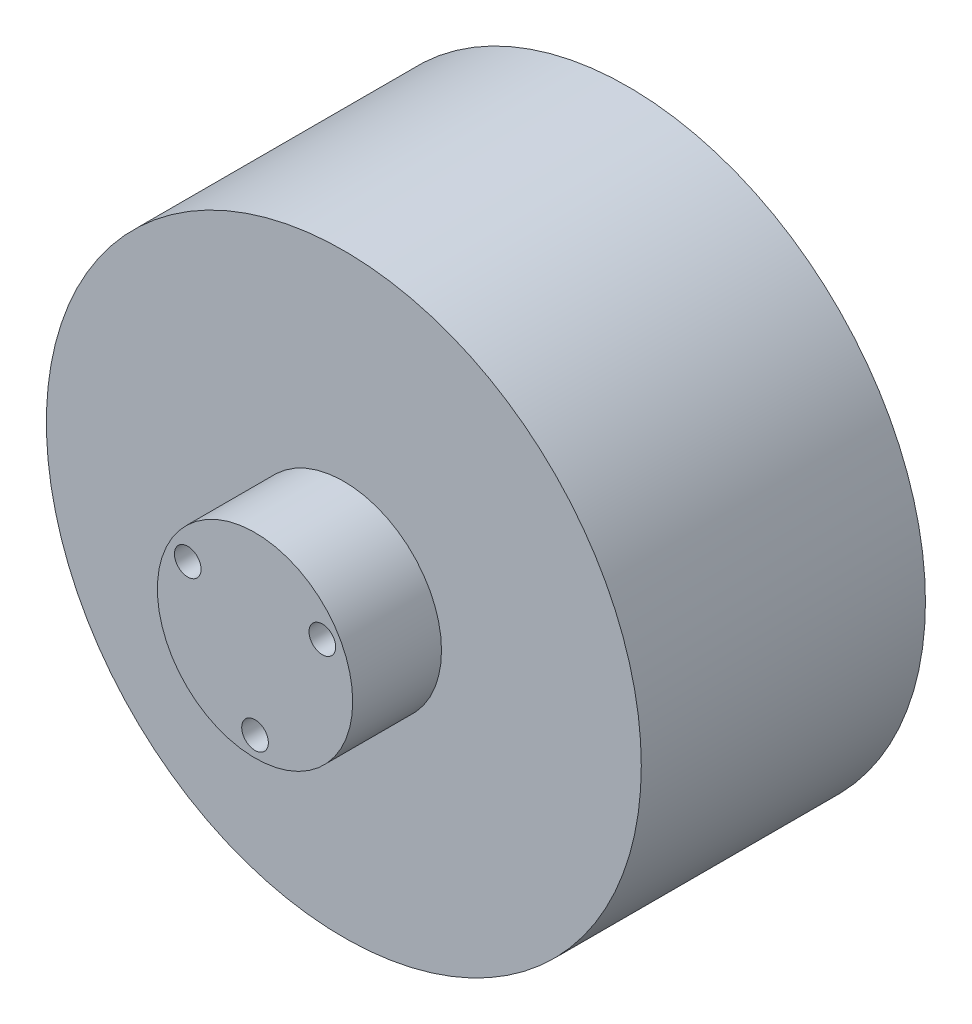
SolidWorks part; units mm, degrees
ref_plane "前视基准面" through (0, 0, 0) normal (0, 0, 1) x (1, 0, 0)
ref_plane "上视基准面" through (0, 0, 0) normal (0, 1, 0) x (1, 0, 0)
ref_plane "右视基准面" through (0, 0, 0) normal (1, 0, 0) x (0, 0, -1)
sketch "草图1" plane through (0, 0, 0) normal (0, 0, 1) x (1, 0, 0)
  circle A0 centre (0, 0) radius 16.5
  dimension "D1" = 33
extrude "凸台-拉伸1" add sketch "草图1" along normal blind 2.5
sketch "草图2" plane through (0, 0, 2.5) normal (0, 0, 1) x (1, 0, 0)
  circle A0 centre (0, 0) radius 33.5
  dimension "D1" = 67
extrude "凸台-拉伸2" add sketch "草图2" along normal blind 32
sketch "草图3" plane through (0, 0, 34.5) normal (0, 0, 1) x (1, 0, 0)
  circle A0 centre (0, 0) radius 11
  dimension "D1" = 22
extrude "凸台-拉伸3" add sketch "草图3" along normal blind 10
sketch "草图4" plane through (0, 0, 44.5) normal (0, 0, 1) x (1, 0, 0)
  line L0 (0, 0) -> (0, -8.75) construction
  circle A0 centre (0, 0) radius 8.75 construction
  circle A1 centre (0, -8.75) radius 1.5
  circle A2 centre (-7.5777, 4.375) radius 1.5
  circle A3 centre (7.5777, 4.375) radius 1.5
  point P11 (0, 0)
  dimension "D1" = 17.5
  dimension "D2" = 3
  dimension "D3" = 3
extrude "切除-拉伸1" cut sketch "草图4" against normal blind 5 contours A3 | A2 | A1
sketch "草图5" plane through (0, 0, 0) normal (0, 0, -1) x (-1, 0, 0)
  line L0 (0, 0) -> (0, -14) construction
  circle A0 centre (0, 0) radius 14 construction
  circle A1 centre (0, -14) radius 1.5
  circle A2 centre (-12.1244, 7) radius 1.5
  circle A3 centre (12.1244, 7) radius 1.5
  point P11 (0, 0)
  dimension "D1" = 28
  dimension "D2" = 3
  dimension "D3" = 3
extrude "切除-拉伸2" cut sketch "草图5" against normal blind 5
